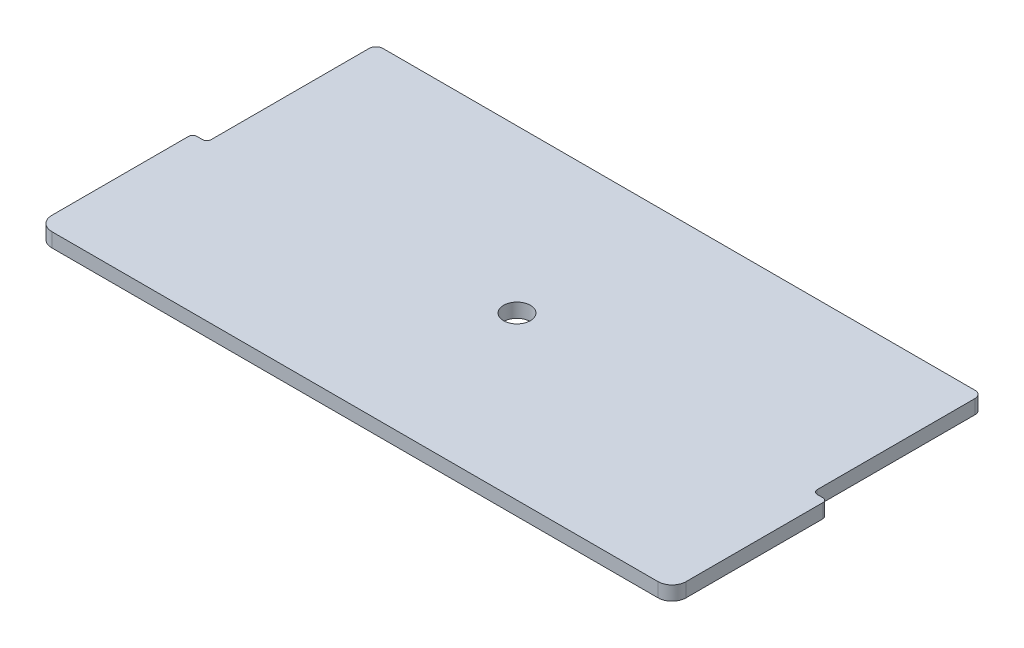
SolidWorks part; units mm, degrees
ref_plane "Front Plane" through (0, 0, 0) normal (0, 0, 1) x (1, 0, 0)
ref_plane "Top Plane" through (0, 0, 0) normal (0, 1, 0) x (1, 0, 0)
ref_plane "Right Plane" through (0, 0, 0) normal (1, 0, 0) x (0, 0, -1)
sketch "Sketch2" plane through (0, 0, 0) normal (0, 1, 0) x (1, 0, 0)
  line L5 (-48.1701, 30.9285) -> (401.8299, 30.9285)
  line L6 (-48.1701, 30.9285) -> (-48.1701, -199.0715)
  line L7 (-48.1701, -199.0715) -> (401.8299, -199.0715)
  line L8 (401.8299, 30.9285) -> (401.8299, -199.0715)
  dimension "D1" = 450
  dimension "D2" = 230
extrude "Boss-Extrude2" add sketch "Sketch2" along normal blind 10
sketch "Sketch4" plane through (0, 10, 0) normal (0, 1, 0) x (1, 0, 0)
  line L0 (-48.1701, 30.9285) -> (-48.1701, -199.0715) construction
  line L1 (-48.1701, 30.9285) -> (-38.1701, 30.9285)
  line L2 (-48.1701, 30.9285) -> (-48.1701, -89.0715)
  line L3 (-48.1701, -89.0715) -> (-38.1701, -89.0715)
  line L4 (-38.1701, 30.9285) -> (-38.1701, -89.0715)
  line L5 (-48.1701, -199.0715) -> (401.8299, -199.0715) construction
  line L11 (401.8299, -199.0715) -> (401.8299, 30.9285) construction
  line L12 (401.8299, -89.0715) -> (391.8299, -89.0715)
  line L13 (401.8299, -89.0715) -> (401.8299, 30.9285)
  line L14 (401.8299, 30.9285) -> (391.8299, 30.9285)
  line L15 (391.8299, -89.0715) -> (391.8299, 30.9285)
  line L16 (401.8299, 30.9285) -> (-48.1701, 30.9285) construction
  dimension "D1" = 110
  dimension "D2" = 120
  dimension "D3" = 10
  dimension "D4" = 110
  dimension "D5" = 120
  dimension "D6" = 10
extrude "Cut-Extrude2" cut sketch "Sketch4" against normal blind 286
fillet "Fillet1" radius 10 1 edges at (-48.1701, 5, 199.0715)
fillet "Fillet7" radius 3 2 edges at (-38.1701, 5, 89.0715) (-48.1701, 5, 89.0715)
fillet "Fillet8" radius 5 2 edges at (391.8299, 5, -30.9285) (-38.1701, 5, -30.9285)
fillet "Fillet9" radius 3 2 edges at (401.8299, 5, 89.0715) (391.8299, 5, 89.0715)
fillet "Fillet10" radius 10 1 edges at (401.8299, 5, 199.0715)
sketch "Sketch5" plane through (0, 10, 0) normal (0, 1, 0) x (1, 0, 0)
  line L1 (386.8299, 30.9285) -> (-33.1701, 30.9285) construction
  line L3 (-38.1701, -86.0715) -> (-38.1701, 25.9285) construction
  circle A0 centre (176.8299, -84.0715) radius 9.5
  dimension "D2" = 215
  dimension "D1" = 115
extrude "Cut-Extrude4" cut sketch "Sketch5" against normal blind 10
